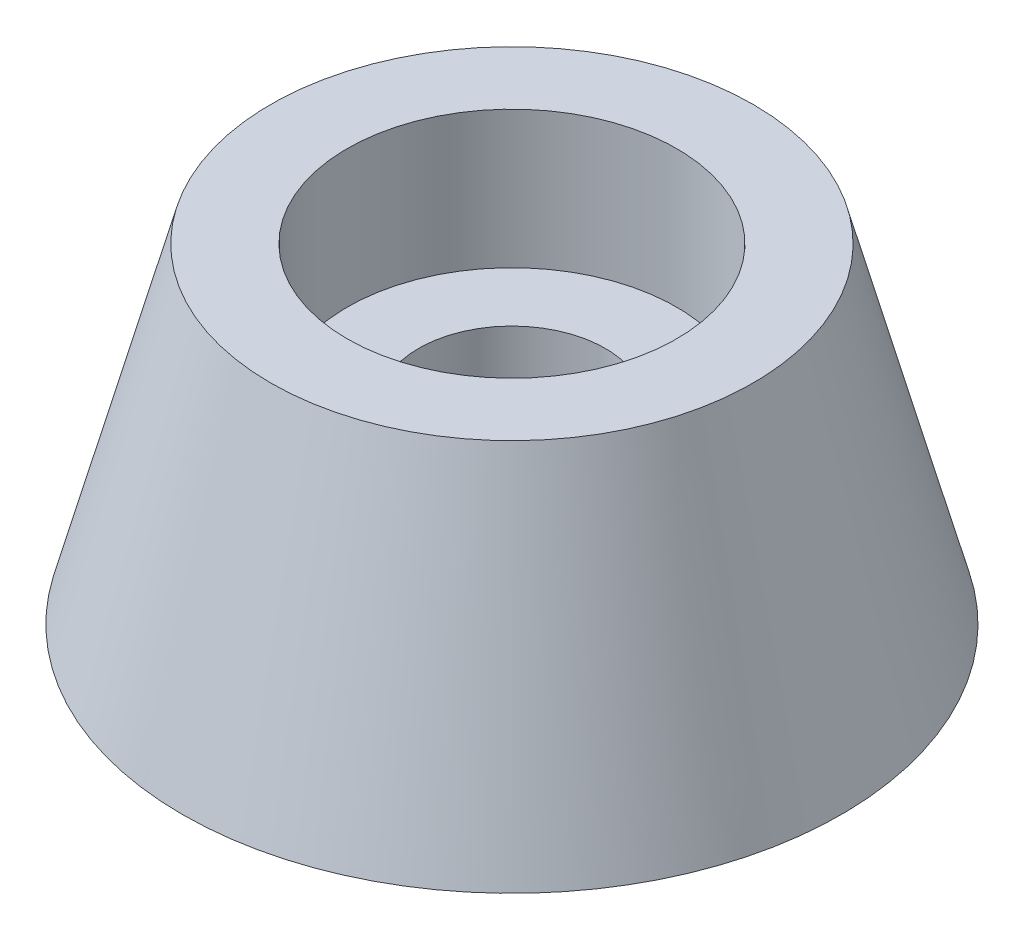
SolidWorks part; units mm, degrees
ref_plane "Plan de face" through (0, 0, 0) normal (0, 0, 1) x (1, 0, 0)
ref_plane "Plan de dessus" through (0, 0, 0) normal (0, 1, 0) x (1, 0, 0)
ref_plane "Plan de droite" through (0, 0, 0) normal (1, 0, 0) x (0, 0, -1)
sketch "Esquisse1" plane through (0, 0, 0) normal (0, 1, 0) x (1, 0, 0)
  circle A0 centre (0, 0) radius 6
  dimension "D1" = 12
extrude "Boss.-Extru.1" add sketch "Esquisse1" along normal blind 6 draft 15
sketch "Esquisse2" plane through (0, 6, 0) normal (0, 1, 0) x (1, 0, 0)
  circle A0 centre (0, 0) radius 3
  dimension "D1" = 6
extrude "Enlèv. mat.-Extru.1" cut sketch "Esquisse2" against normal offset from surface (2.5 mm away) 3.5 up to face at (0, 0, 6)
hole_wizard "Dégagement M31" positions "Esquisse3" profile "Esquisse4" hole size "M3" standard "ISO" end condition through all
sketch "Esquisse3" plane through (0, 3.5, 0) normal (0, 1, 0) x (1, 0, 0)
  point P0 (0, 0)
sketch "Esquisse4" plane through (0, 3.5, 0) normal (1, 0, 0) x (0, 0, 1)
  line L0 (0, 0) -> (0, 3.5)
  line L1 (0, 3.5) -> (1.7, 3.5)
  line L2 (1.7, 3.5) -> (1.7, 0)
  line L5 (1.7, 0) -> (0, 0)
  line L11 (0, -6.35) -> (0, 107.95) construction
  dimension "Diamètre du perçage jusqu'au prochain" = 3.4
  dimension "Profondeur du perçage jusqu'au prochain" = 3.5
